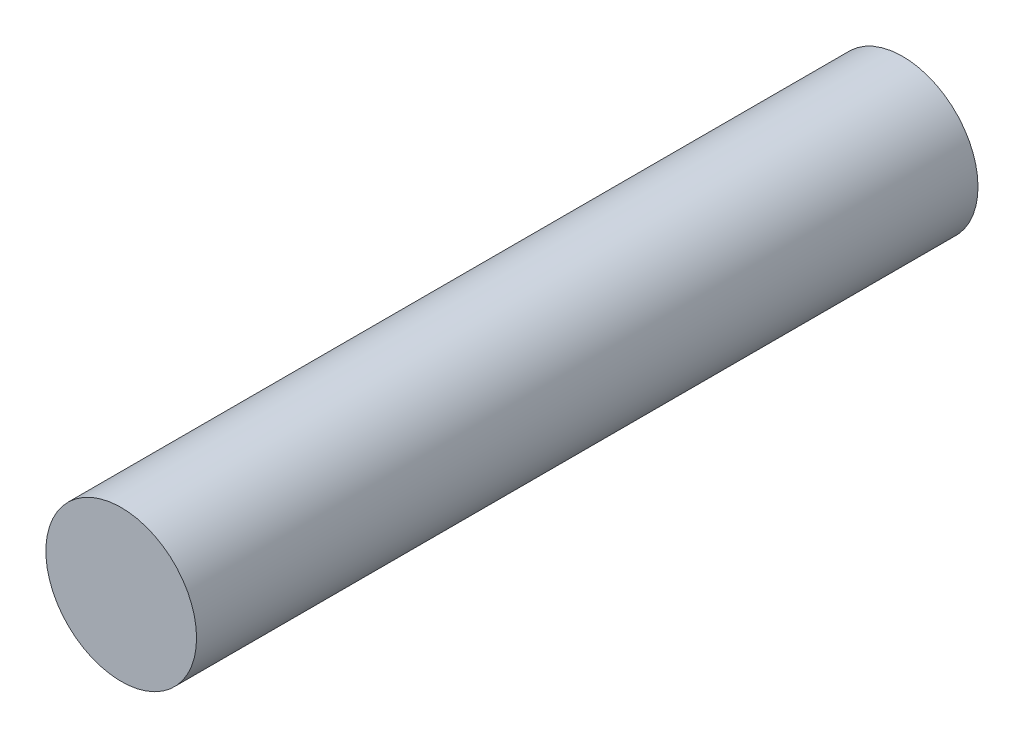
SolidWorks part; units mm, degrees
ref_plane "Front Plane" through (0, 0, 0) normal (0, 0, 1) x (1, 0, 0)
ref_plane "Top Plane" through (0, 0, 0) normal (0, 1, 0) x (1, 0, 0)
ref_plane "Right Plane" through (0, 0, 0) normal (1, 0, 0) x (0, 0, -1)
sketch "Sketch1" plane through (0, 0, 0) normal (0, 0, 1) x (1, 0, 0)
  circle A0 centre (0, 0) radius 1.35
  dimension "D1" = 2.7
extrude "Boss-Extrude1" add sketch "Sketch1" along normal blind 14
